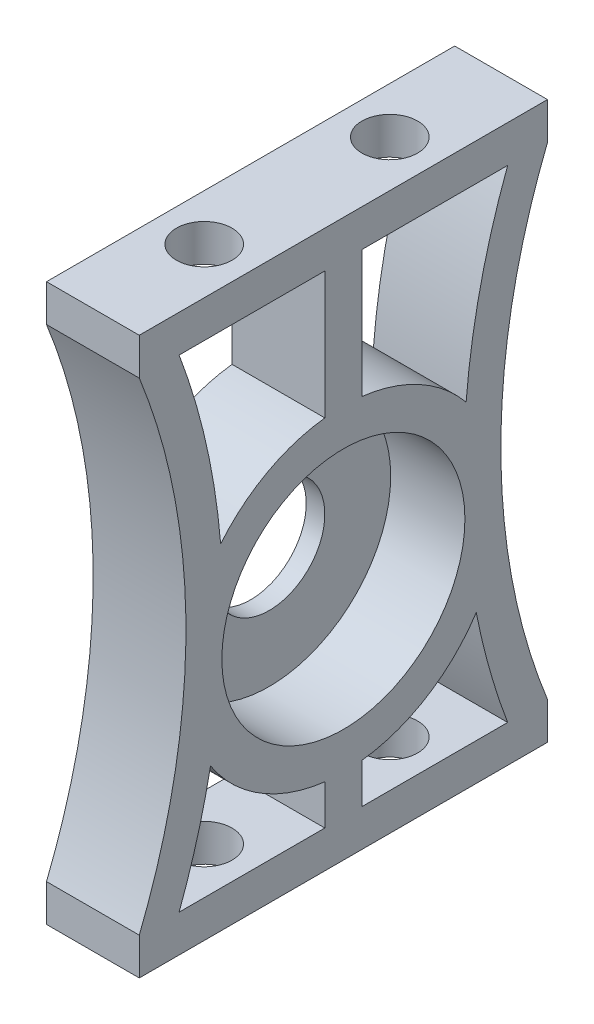
SolidWorks part; units mm, degrees
ref_plane "前基準面" through (0, 0, 0) normal (0, 0, 1) x (1, 0, 0)
ref_plane "上基準面" through (0, 0, 0) normal (0, 1, 0) x (1, 0, 0)
ref_plane "右基準面" through (0, 0, 0) normal (1, 0, 0) x (0, 0, -1)
sketch "Sketch1" plane through (0, 0, 0) normal (1, 0, 0) x (0, 0, -1)
  line L0 (0, 0) -> (0, -12.65) construction
  line L1 (0, -12.65) -> (0, 17.35) construction
  line L2 (-11, -12.65) -> (11, -12.65) construction
  line L3 (-8.854, -10.65) -> (-8.854, -10.65)
  line L4 (-11, -12.65) -> (11, -12.65) construction
  line L5 (-11, -12.65) -> (-11, 17.35) construction
  line L6 (-11, 17.35) -> (11, 17.35) construction
  line L7 (11, -12.65) -> (11, 17.35) construction
  line L8 (-11, 17.35) -> (11, 17.35)
  line L9 (-11, 17.35) -> (-11, 15.35)
  line L10 (-11, 15.35) -> (11, 15.35) construction
  line L11 (11, 17.35) -> (11, 15.35)
  line L12 (-11, -12.65) -> (11, -12.65)
  line L13 (-11, -12.65) -> (-11, -10.65)
  line L14 (-11, -10.65) -> (11, -10.65) construction
  line L15 (11, -12.65) -> (11, -10.65)
  line L16 (-8.854, -10.65) -> (8.854, -10.65)
  line L17 (8.854, -10.65) -> (8.854, -10.65)
  line L18 (8.854, 15.35) -> (8.854, 15.35)
  line L19 (-8.854, 15.35) -> (8.854, 15.35)
  line L20 (-8.854, 15.35) -> (-8.854, 15.35)
  circle A0 centre (0, 0) radius 6.55
  circle A1 centre (0, 0) radius 8.55 construction
  arc A2 (-11, 15.35) -> (-11, -10.65) centre (-43.3598, 2.35) cw
  arc A3 (11, 15.35) -> (11, -10.65) centre (43.3598, 2.35) ccw
  arc A4 (-8.854, 15.35) -> (-8.854, -10.65) centre (-43.3598, 2.35) cw construction
  arc A5 (8.854, 15.35) -> (8.854, -10.65) centre (43.3598, 2.35) ccw construction
  arc A6 (-8.854, 15.35) -> (-6.6142, 5.418) centre (-43.3598, 2.35) cw
  arc A7 (-6.6142, 5.418) -> (6.6142, 5.418) centre (0, 0) cw
  arc A8 (-8.854, -10.65) -> (-7.161, -4.6714) centre (-43.3598, 2.35) ccw
  arc A9 (-7.161, -4.6714) -> (7.161, -4.6714) centre (0, 0) ccw
  arc A10 (8.854, 15.35) -> (6.6142, 5.418) centre (43.3598, 2.35) ccw
  arc A11 (8.854, -10.65) -> (7.161, -4.6714) centre (43.3598, 2.35) cw
  point P8 (0, -12.65)
  dimension "D1" = 13.1
  dimension "D8" = 2
  dimension "D9" = 2
  dimension "D2" = 12.65
  dimension "D3" = 30
  dimension "D4" = 22
  dimension "D5" = 30
  dimension "D6" = 2
  dimension "D7" = 2
extrude "Boss-Extrude4" add sketch "Sketch1" along normal blind 5 contours A3 L11 L8 L9 A2 L13 L12 L15 A11 L16 A8 A9 A0 L19 A10 A7 A6
sketch "Sketch3" plane through (5, 0, 0) normal (1, 0, 0) x (0, 0, -1)
  line L0 (0, 17.35) -> (0, -12.65) construction
  line L1 (-11, 17.35) -> (11, 17.35) construction
  line L2 (-11, -12.65) -> (11, -12.65) construction
  line L3 (-8.854, 15.35) -> (8.854, 15.35) construction
  line L4 (-1, 6.55) -> (1, 6.55)
  line L5 (-1, 6.55) -> (-1, 15.35)
  line L6 (-1, 15.35) -> (1, 15.35)
  line L7 (1, 6.55) -> (1, 15.35)
  line L8 (0, 15.35) -> (0, 6.55) construction
  line L9 (-1, 10.95) -> (1, 10.95) construction
  line L10 (-8.854, -10.65) -> (8.854, -10.65) construction
  line L11 (-1, -6.55) -> (1, -6.55)
  line L12 (-1, -6.55) -> (-1, -10.65)
  line L13 (-1, -10.65) -> (1, -10.65)
  line L14 (1, -6.55) -> (1, -10.65)
  line L15 (0, -10.65) -> (0, -6.55) construction
  line L16 (-1, -8.6) -> (1, -8.6) construction
  circle A0 centre (0, 0) radius 6.55 construction
  point P6 (0, 10.95)
  point P14 (0, -8.6)
  dimension "D1" = 2
extrude "Boss-Extrude5" add sketch "Sketch3" against normal blind 5
sketch "Sketch4" plane through (0, 0, 0) normal (-1, 0, 0) x (0, 0, 1)
  circle A0 centre (0, 0) radius 6.55 construction
  circle A1 centre (0, 0) radius 6.55
  circle A2 centre (0, 0) radius 3
  dimension "D1" = 6
extrude "Boss-Extrude6" add sketch "Sketch4" against normal blind 1
sketch "Sketch5" plane through (0, -12.65, 0) normal (0, -1, 0) x (1, 0, 0)
  line L0 (2.5, 11) -> (2.5, -11) construction
  line L1 (5, 11) -> (0, 11) construction
  line L2 (5, -11) -> (0, -11) construction
  line L3 (5, 1) -> (0, 1) construction
  line L4 (0, 1) -> (0, 8.854) construction
  line L5 (0, 8.854) -> (5, 8.854) construction
  line L6 (5, 8.854) -> (5, 1) construction
  line L7 (0, -1) -> (5, -1) construction
  line L8 (5, -1) -> (5, -8.854) construction
  line L9 (5, -8.854) -> (0, -8.854) construction
  line L10 (0, -8.854) -> (0, -1) construction
  line L11 (5, 1) -> (0, 1) construction
  line L12 (0, 1) -> (0, 8.854) construction
  line L13 (0, 8.854) -> (5, 8.854) construction
  line L14 (5, 8.854) -> (5, 1) construction
  line L15 (0, -1) -> (5, -1) construction
  line L16 (5, -1) -> (5, -8.854) construction
  line L17 (5, -8.854) -> (0, -8.854) construction
  line L18 (0, -8.854) -> (0, -1) construction
  line L19 (0, 0) -> (5, 0) construction
  line L20 (5, 11) -> (5, -11) construction
  circle A0 centre (2.5, 5) radius 1.5
  circle A1 centre (2.5, -5) radius 1.5
  dimension "D1" = 3
  dimension "D2" = 5
extrude "Cut-Extrude1" cut sketch "Sketch5" against normal up to next
sketch "Sketch6" plane through (0, 17.35, 0) normal (0, 1, 0) x (1, 0, 0)
  circle A0 centre (2.5, -5) radius 1.5 construction
  circle A1 centre (2.5, 5) radius 1.5 construction
  circle A2 centre (2.5, -5) radius 1.5
  circle A3 centre (2.5, 5) radius 1.5
extrude "Cut-Extrude2" cut sketch "Sketch6" against normal up to next
